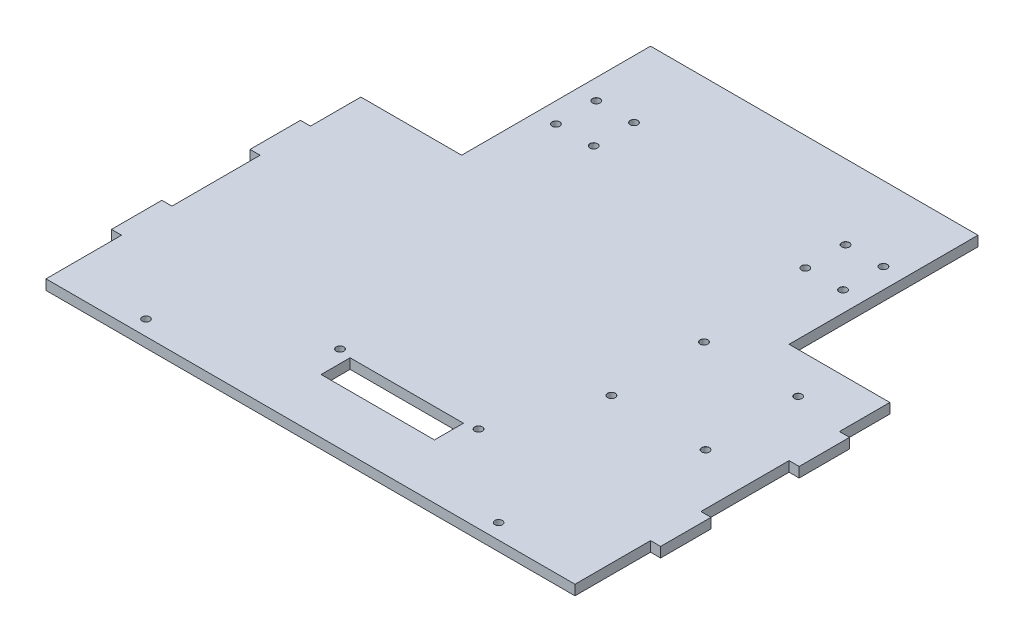
SolidWorks part; units mm, degrees
ref_plane "Front Plane" through (0, 0, 0) normal (0, 0, 1) x (1, 0, 0)
ref_plane "Top Plane" through (0, 0, 0) normal (0, 1, 0) x (1, 0, 0)
ref_plane "Right Plane" through (0, 0, 0) normal (1, 0, 0) x (0, 0, -1)
sketch "Sketch1" plane through (0, 0, 0) normal (0, 1, 0) x (1, 0, 0)
  line L1 (0, 0) -> (210, 0)
  line L2 (0, 0) -> (0, 200)
  line L3 (0, 200) -> (210, 200)
  line L4 (210, 0) -> (210, 200)
  dimension "D1" = 200
  dimension "D2" = 210
extrude "Boss-Extrude1" add sketch "Sketch1" along normal blind 4
sketch "Sketch2" plane through (0, 4, 0) normal (0, 1, 0) x (1, 0, 0)
  line L0 (170, 200) -> (210, 200)
  line L1 (0, 200) -> (40, 200)
  line L2 (0, 200) -> (0, 125)
  line L3 (0, 125) -> (40, 125)
  line L4 (40, 200) -> (40, 125)
  line L5 (170, 200) -> (170, 125)
  line L6 (170, 125) -> (210, 125)
  line L7 (210, 200) -> (210, 125)
  dimension "D1" = 75
  dimension "D2" = 40
  dimension "D3" = 75
  dimension "D4" = 40
extrude "Cut-Extrude1" cut sketch "Sketch2" against normal through all
sketch "Sketch3" plane through (0, 4, 0) normal (0, 1, 0) x (1, 0, 0)
  line L0 (40, 200) -> (40, 162.5) construction
  line L1 (40, 125) -> (40, 200) construction
  line L2 (40, 162.5) -> (40, 125) construction
sketch "Sketch4" plane through (0, 4, 0) normal (0, 1, 0) x (1, 0, 0)
  line L0 (210, 17.4959) -> (141, 17.4959) construction
  line L1 (210, 0) -> (210, 125) construction
  line L2 (141, 0) -> (141, 39.6985) construction
  line L3 (0, 0) -> (210, 0) construction
  dimension "D1" = 69
sketch "Sketch5" plane through (210, 0, 0) normal (1, 0, 0) x (0, 0, -1)
  line L0 (0, 4) -> (125, 4) construction
  line L1 (105, 4) -> (85, 4)
  line L2 (105, 4) -> (105, 0)
  line L3 (105, 0) -> (85, 0)
  line L4 (85, 4) -> (85, 0)
  line L5 (0, 0) -> (125, 0) construction
  line L6 (50, 4) -> (30, 4)
  line L7 (50, 4) -> (50, 0)
  line L8 (50, 0) -> (30, 0)
  line L9 (30, 4) -> (30, 0)
  line L10 (125, 0) -> (125, 4) construction
  dimension "D1" = 20
  dimension "D3" = 20
  dimension "D4" = 35
  dimension "D2" = 2
extrude "Boss-Extrude2" add sketch "Sketch5" along normal blind 4
sketch "Sketch6" plane through (0, 0, 0) normal (-1, 0, 0) x (0, 0, 1)
  line L7 (-125, 4) -> (0, 4) construction
  line L8 (-85, 4) -> (-105, 4)
  line L9 (-85, 4) -> (-85, 0)
  line L10 (-85, 0) -> (-105, 0)
  line L11 (-105, 4) -> (-105, 0)
  line L12 (-125, 0) -> (0, 0) construction
  line L13 (-125, 0) -> (-125, 4) construction
  line L14 (-30, 4) -> (-50, 4)
  line L15 (-30, 4) -> (-30, 0)
  line L16 (-30, 0) -> (-50, 0)
  line L17 (-50, 4) -> (-50, 0)
  dimension "D1" = 20
  dimension "D2" = 20
  dimension "D4" = 35
  dimension "D3" = 2
extrude "Boss-Extrude3" add sketch "Sketch6" along normal blind 4
hole_wizard "Ø3.0mm Dowel Hole1" positions "Sketch9" profile "Sketch8" hole size "Ø3.0" standard "ISO" end condition through all
sketch "Sketch9" plane through (0, 4, 0) normal (0, 1, 0) x (1, 0, 0)
  point P0 (137.5, 34.21)
  point P3 (82.5, 34.2242)
  point P6 (162, 170.4328)
  point P9 (162, 154.4328)
  point P12 (147, 154.4328)
  point P15 (147, 170.4328)
  point P18 (63, 170.4328)
  point P21 (48, 170.4328)
  point P24 (48, 154.4328)
  point P27 (63, 154.4328)
  point P30 (189.7045, 108.8921)
  point P33 (189.7045, 72.1503)
  point P36 (152.325, 72.1503)
  point P39 (152.325, 108.8921)
sketch "Sketch8" plane through (137.5, 4, -34.21) normal (1, 0, 0) x (0, 0, 1)
  line L0 (0, 0) -> (0, 4)
  line L1 (0, 4) -> (1.5, 4)
  line L2 (1.5, 4) -> (1.5, 0.025)
  line L3 (1.5, 0.025) -> (1.525, 0)
  line L5 (1.525, 0) -> (0, 0)
  line L6 (-1.5, 0.025) -> (-1.525, 0) construction
  line L11 (0, -6.35) -> (0, 107.95) construction
  dimension "Thru Hole Dia." = 3
  dimension "Thru Hole Depth" = 4
  dimension "Near C'Sink Dia." = 3.05
  dimension "Near C'Sink Angle" = 90
sketch "Sketch10" plane through (0, 4, 0) normal (0, 1, 0) x (1, 0, 0)
  line L1 (132.5, 33.2242) -> (87.5, 33.2242)
  line L2 (132.5, 33.2242) -> (132.5, 21.7242)
  line L3 (132.5, 21.7242) -> (87.5, 21.7242)
  line L4 (87.5, 33.2242) -> (87.5, 21.7242)
extrude "Cut-Extrude2" cut sketch "Sketch10" against normal through all
hole_wizard "Ø3.0mm Dowel Hole2" positions "Sketch11" profile "Sketch12" hole size "Ø3.0" standard "ISO" end condition through all
sketch "Sketch11" plane through (0, 0, 0) normal (0, -1, 0) x (-1, 0, 0)
  point P0 (-33.6603, 6.0284)
  point P3 (-173.6603, 6.0284)
sketch "Sketch12" plane through (33.6603, 0, -6.0284) normal (1, 0, 0) x (0, 0, -1)
  line L0 (0, 0) -> (0, 4)
  line L1 (0, 4) -> (1.5, 4)
  line L2 (1.5, 4) -> (1.5, 0.025)
  line L3 (1.5, 0.025) -> (1.525, 0)
  line L5 (1.525, 0) -> (0, 0)
  line L6 (-1.5, 0.025) -> (-1.525, 0) construction
  line L11 (0, -6.35) -> (0, 107.95) construction
  dimension "Thru Hole Dia." = 3
  dimension "Thru Hole Depth" = 4
  dimension "Near C'Sink Dia." = 3.05
  dimension "Near C'Sink Angle" = 90
